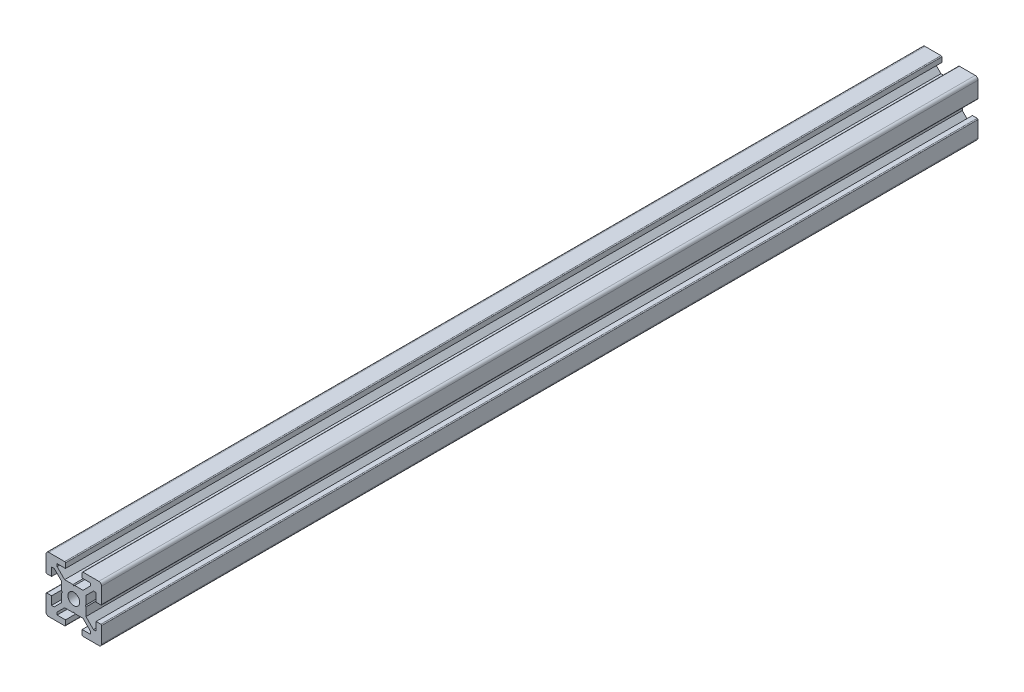
SolidWorks part; units mm, degrees
ref_plane "Front Plane" through (0, 0, 0) normal (0, 0, 1) x (1, 0, 0)
ref_plane "Top Plane" through (0, 0, 0) normal (0, 1, 0) x (1, 0, 0)
ref_plane "Right Plane" through (0, 0, 0) normal (1, 0, 0) x (0, 0, -1)
sketch "Sketch1" plane through (0, 0, 0) normal (0, 0, 1) x (1, 0, 0)
  line L0 (0, 0) -> (0, 4.3607) construction
  line L1 (-10, 10) -> (10, 10) construction
  line L2 (-10, 10) -> (-10, -10) construction
  line L3 (-10, -10) -> (10, -10) construction
  line L4 (10, 10) -> (10, -10) construction
  line L5 (-10, 10) -> (10, -10) construction
  line L6 (-10, -10) -> (10, 10) construction
  line L7 (0, 4.3607) -> (3.3, 4.3607) construction
  line L8 (3.3, 4.3607) -> (6, 7.0607)
  line L9 (6, 7.0607) -> (6, 8)
  line L10 (6, 8) -> (3, 8)
  line L11 (3, 8) -> (3, 9.7)
  line L12 (3.3, 10) -> (9, 10)
  line L13 (0, 4.0607) -> (0.3, 4.3607)
  line L14 (0.3, 4.3607) -> (3.3, 4.3607)
  line L15 (10, 3.3) -> (10, 9)
  line L16 (8, 3) -> (9.7, 3)
  line L17 (8, 6) -> (8, 3)
  line L18 (7.0607, 6) -> (8, 6)
  line L19 (4.3607, 3.3) -> (7.0607, 6)
  line L20 (4.3607, 0.3) -> (4.3607, 3.3)
  line L21 (4.0607, 0) -> (4.3607, 0.3)
  line L22 (4.0607, 0) -> (4.3607, -0.3)
  line L23 (4.3607, -0.3) -> (4.3607, -3.3)
  line L24 (4.3607, -3.3) -> (7.0607, -6)
  line L25 (7.0607, -6) -> (8, -6)
  line L26 (8, -6) -> (8, -3)
  line L27 (8, -3) -> (9.7, -3)
  line L28 (10, -3.3) -> (10, -9)
  line L29 (3.3, -10) -> (9, -10)
  line L30 (3, -8) -> (3, -9.7)
  line L31 (6, -8) -> (3, -8)
  line L32 (6, -7.0607) -> (6, -8)
  line L33 (3.3, -4.3607) -> (6, -7.0607)
  line L34 (0.3, -4.3607) -> (3.3, -4.3607)
  line L35 (0, -4.0607) -> (0.3, -4.3607)
  line L36 (0, -4.0607) -> (-0.3, -4.3607)
  line L37 (-0.3, -4.3607) -> (-3.3, -4.3607)
  line L38 (-3.3, -4.3607) -> (-6, -7.0607)
  line L39 (-6, -7.0607) -> (-6, -8)
  line L40 (-6, -8) -> (-3, -8)
  line L41 (-3, -8) -> (-3, -9.7)
  line L42 (-3.3, -10) -> (-9, -10)
  line L43 (-10, -3.3) -> (-10, -9)
  line L44 (-8, -3) -> (-9.7, -3)
  line L45 (-8, -6) -> (-8, -3)
  line L46 (-7.0607, -6) -> (-8, -6)
  line L47 (-4.3607, -3.3) -> (-7.0607, -6)
  line L48 (-4.3607, -0.3) -> (-4.3607, -3.3)
  line L49 (-4.0607, 0) -> (-4.3607, -0.3)
  line L50 (-4.0607, 0) -> (-4.3607, 0.3)
  line L51 (-4.3607, 0.3) -> (-4.3607, 3.3)
  line L52 (-4.3607, 3.3) -> (-7.0607, 6)
  line L53 (-7.0607, 6) -> (-8, 6)
  line L54 (-8, 6) -> (-8, 3)
  line L55 (-8, 3) -> (-9.7, 3)
  line L56 (-10, 3.3) -> (-10, 9)
  line L57 (-3.3, 10) -> (-9, 10)
  line L58 (-3, 8) -> (-3, 9.7)
  line L59 (-6, 8) -> (-3, 8)
  line L60 (-6, 7.0607) -> (-6, 8)
  line L61 (-3.3, 4.3607) -> (-6, 7.0607)
  line L62 (-0.3, 4.3607) -> (-3.3, 4.3607)
  line L63 (0, 4.0607) -> (-0.3, 4.3607)
  arc A0 (3, 9.7) -> (3.3, 10) centre (3.3, 9.7) cw
  arc A1 (9, 10) -> (10, 9) centre (9, 9) cw
  arc A2 (9.7, 3) -> (10, 3.3) centre (9.7, 3.3) ccw
  arc A3 (9.7, -3) -> (10, -3.3) centre (9.7, -3.3) cw
  arc A4 (10, -9) -> (9, -10) centre (9, -9) cw
  arc A5 (3, -9.7) -> (3.3, -10) centre (3.3, -9.7) ccw
  arc A6 (-3, -9.7) -> (-3.3, -10) centre (-3.3, -9.7) cw
  arc A7 (-9, -10) -> (-10, -9) centre (-9, -9) cw
  arc A8 (-9.7, -3) -> (-10, -3.3) centre (-9.7, -3.3) ccw
  arc A9 (-9.7, 3) -> (-10, 3.3) centre (-9.7, 3.3) cw
  arc A10 (-10, 9) -> (-9, 10) centre (-9, 9) cw
  arc A11 (-3, 9.7) -> (-3.3, 10) centre (-3.3, 9.7) ccw
  circle A12 centre (0, 0) radius 2.1
  point P0 (0, 0)
  point P95 (0, 0)
  dimension "D4" = 1
  dimension "D5" = 0.3
  dimension "D12" = 4.2
  dimension "D1" = 20
  dimension "D2" = 20
  dimension "D3" = 2
  dimension "D6" = 0.75
  dimension "D7" = 3
  dimension "D8" = 0.9393
  dimension "D9" = 3
  dimension "D10" = 0.3
  dimension "D11" = 4
extrude "Boss-Extrude1" add sketch "Sketch1" along normal blind 315
